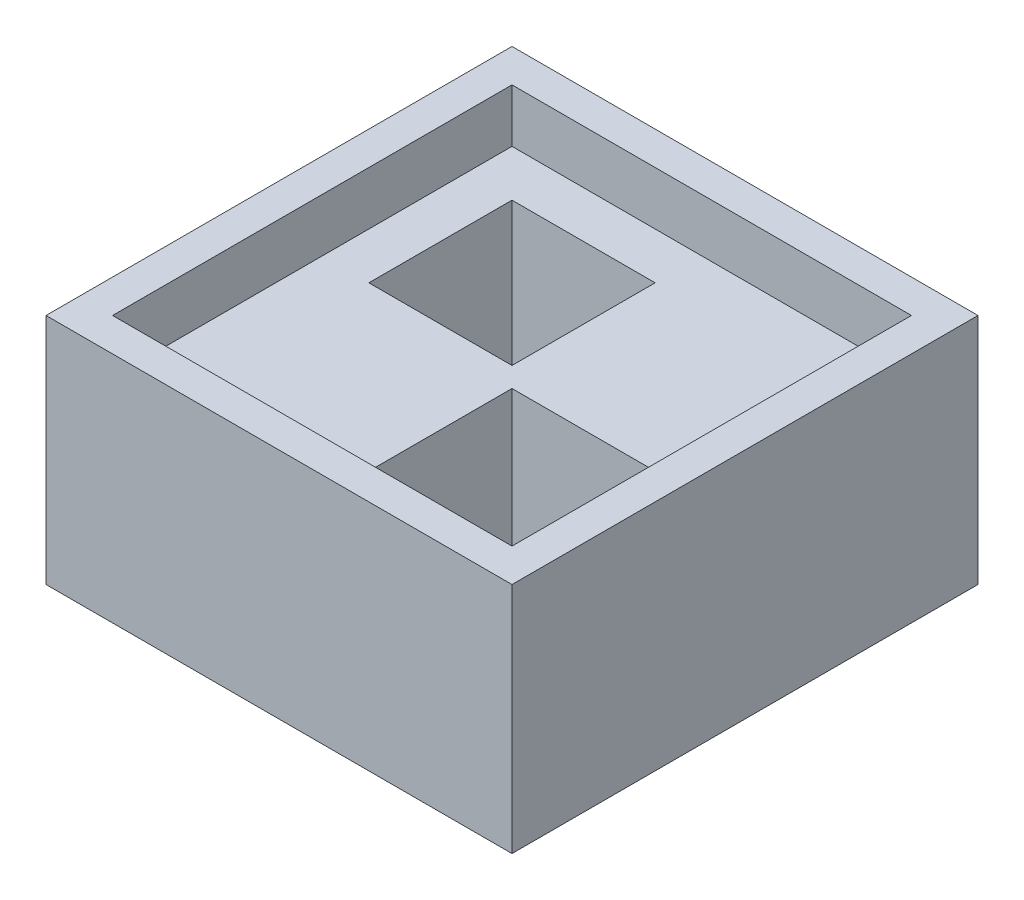
SolidWorks part; units mm, degrees
ref_plane "Front Plane" through (0, 0, 0) normal (0, 0, 1) x (1, 0, 0)
ref_plane "Top Plane" through (0, 0, 0) normal (0, 1, 0) x (1, 0, 0)
ref_plane "Right Plane" through (0, 0, 0) normal (1, 0, 0) x (0, 0, -1)
sketch "Sketch1" plane through (0, 0, 0) normal (0, 1, 0) x (1, 0, 0)
  line L1 (0, 0) -> (70, 0)
  line L2 (0, 0) -> (0, 70)
  line L3 (0, 70) -> (70, 70)
  line L4 (70, 0) -> (70, 70)
  dimension "D1" = 70
  dimension "D2" = 70
extrude "Boss-Extrude1" add sketch "Sketch1" along normal blind 35
sketch "Sketch2" plane through (0, 35, 0) normal (0, 1, 0) x (1, 0, 0)
  line L0 (0, 0) -> (70, 0) construction
  line L1 (5, 5) -> (65, 5)
  line L2 (5, 5) -> (5, 65)
  line L3 (5, 65) -> (65, 65)
  line L4 (65, 5) -> (65, 65)
  line L5 (70, 70) -> (0, 70) construction
  line L6 (70, 0) -> (70, 70) construction
  line L7 (0, 70) -> (0, 0) construction
  dimension "D1" = 5
  dimension "D2" = 5
  dimension "D3" = 5
  dimension "D4" = 5
extrude "Cut-Extrude1" cut sketch "Sketch2" against normal blind 8
sketch "Sketch3" plane through (0, 27, 0) normal (0, 1, 0) x (1, 0, 0)
  line L0 (65, 65) -> (5, 65) construction
  line L9 (12, 58) -> (33.5, 58)
  line L10 (12, 58) -> (12, 36.5)
  line L11 (12, 36.5) -> (33.5, 36.5)
  line L12 (33.5, 58) -> (33.5, 36.5)
  line L13 (58, 12) -> (36.5, 12)
  line L14 (58, 12) -> (58, 33.5)
  line L15 (58, 33.5) -> (36.5, 33.5)
  line L16 (36.5, 12) -> (36.5, 33.5)
  line L17 (5, 65) -> (5, 5) construction
  line L18 (65, 5) -> (65, 65) construction
  line L19 (5, 5) -> (65, 5) construction
  dimension "D1" = 21.5
  dimension "D2" = 21.5
  dimension "D3" = 21.5
  dimension "D4" = 21.5
  dimension "D5" = 7
  dimension "D6" = 7
  dimension "D7" = 7
  dimension "D8" = 7
extrude "Cut-Extrude2" cut sketch "Sketch3" against normal blind 25.5
